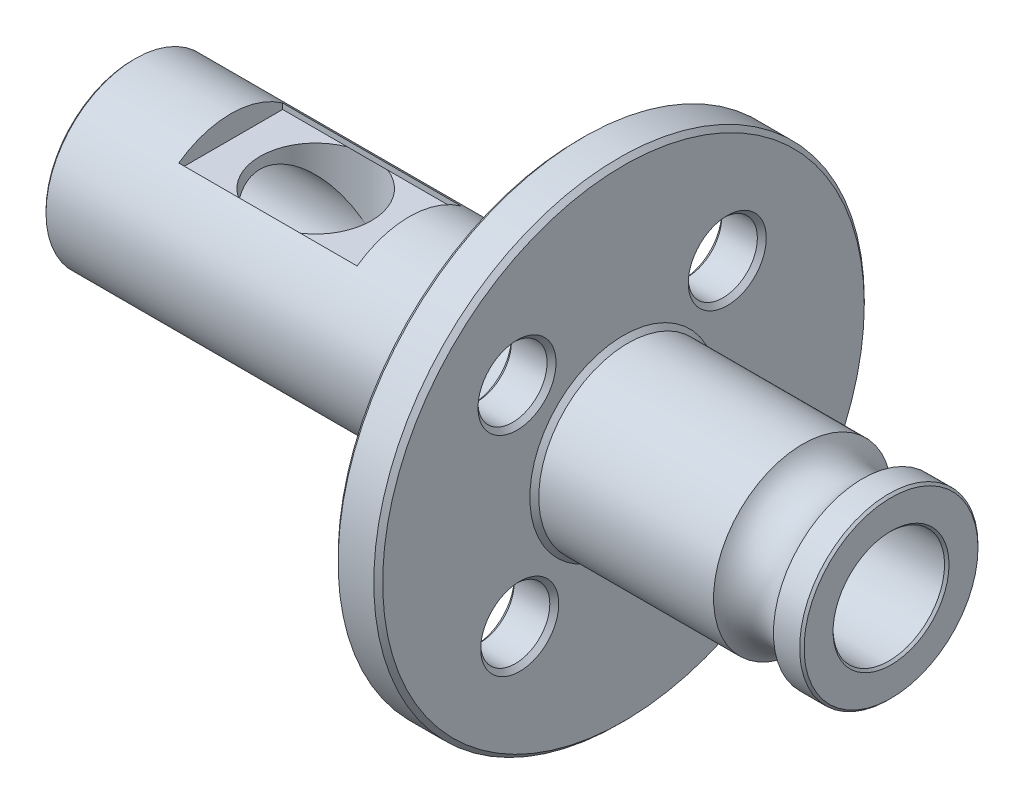
SolidWorks part; units mm, degrees
ref_plane "Front Plane" through (0, 0, 0) normal (0, 0, 1) x (1, 0, 0)
ref_plane "Top Plane" through (0, 0, 0) normal (0, 1, 0) x (1, 0, 0)
ref_plane "Right Plane" through (0, 0, 0) normal (1, 0, 0) x (0, 0, -1)
sketch "Sketch1" plane through (0, 0, 0) normal (0, 1, 0) x (1, 0, 0)
  line L0 (-22, 4) -> (8.0401, 4)
  line L1 (10.7254, 4) -> (12, 4)
  line L2 (12, 4) -> (12, 0)
  line L3 (12, 0) -> (-22, 0)
  line L4 (-22, 0) -> (-22, 4)
  arc A1 (8.0401, 4) -> (10.7254, 4) centre (9.3828, 4.8278) ccw
  dimension "D1" = 4
  dimension "D2" = 34
  dimension "D3" = 12
revolve "Revolve1" add sketch "Sketch1" angle 360 about L3
ref_plane "Plane1" through (0, 0, 0) normal (1, 0, 0) x (0, 0, -1)
sketch "Sketch2" plane through (0, 0, 0) normal (1, 0, 0) x (0, 0, -1)
  circle A0 centre (0, 0) radius 11
  dimension "D1" = 22
extrude "Boss-Extrude1" add sketch "Sketch2" against normal blind 2
sketch "Sketch3" plane through (12, 0, 0) normal (1, 0, 0) x (0, 0, -1)
  circle A0 centre (0, 0) radius 2.5
  dimension "D1" = 5
extrude "Cut-Extrude1" cut sketch "Sketch3" against normal through all
ref_plane "Plane2" through (0, 4, 0) normal (0, 1, 0) x (1, 0, 0)
sketch "Sketch4" plane through (0, 4, 0) normal (0, 1, 0) x (1, 0, 0)
  line L1 (-17.616, 2.33) -> (-9.616, 2.33)
  line L2 (-17.616, 2.33) -> (-17.616, -2.33)
  line L3 (-17.616, -2.33) -> (-9.616, -2.33)
  line L4 (-9.616, 2.33) -> (-9.616, -2.33)
  line L5 (-17.616, 2.33) -> (-9.616, -2.33) construction
  line L6 (-17.616, -2.33) -> (-9.616, 2.33) construction
  point P0 (-13.616, 0)
  point P5 (-14.4525, 0)
  point P7 (-13.616, 0)
  dimension "D1" = 8
  dimension "D2" = 4.66
extrude "Cut-Extrude2" cut sketch "Sketch4" against normal blind 1
sketch "Sketch5" plane through (0, 3, 0) normal (0, 1, 0) x (1, 0, 0)
  circle A0 centre (-13.8043, 0) radius 2.5
  point P2 (-14.5249, 0)
  point P3 (-13.3525, 0)
  point P4 (-13.8043, 0)
  dimension "D1" = 5
extrude "Cut-Extrude3" cut sketch "Sketch5" against normal up to next
sketch "Sketch6" plane through (0, 0, 0) normal (1, 0, 0) x (0, 0, -1)
  circle A0 centre (-4.7764, 4.6544) radius 1.55
  circle A1 centre (4.6544, 4.7764) radius 1.55
  circle A2 centre (4.7764, -4.6544) radius 1.55
  circle A3 centre (-4.6544, -4.7764) radius 1.55
  point P2 (-4.7454, 5.292)
  point P3 (-4.6544, 4.7764)
  point P11 (0, 0)
  dimension "D1" = 3.1
  dimension "D2" = 4
extrude "Cut-Extrude4" cut sketch "Sketch6" against normal through all
chamfer "Chamfer1" distance 0.2 angle 45 12 edges at (-2, 0, -11) (-2, 0, -4) (-2, 4.6544, 3.2264) (-2, 4.7764, -6.2044) (-2, -4.6544, -6.3264) (-2, -4.7764, 3.1044) (0, 0, -11) (0, 0, -4) (0, 4.6544, 3.2264) (0, 4.7764, -6.2044) (0, -4.6544, -6.3264) (0, -4.7764, 3.1044)
chamfer "Chamfer2" distance 0.1 angle 45 4 edges at (12, 0, -4) (12, 0, -2.5) (-22, 0, -4) (-22, 0, -2.5)
